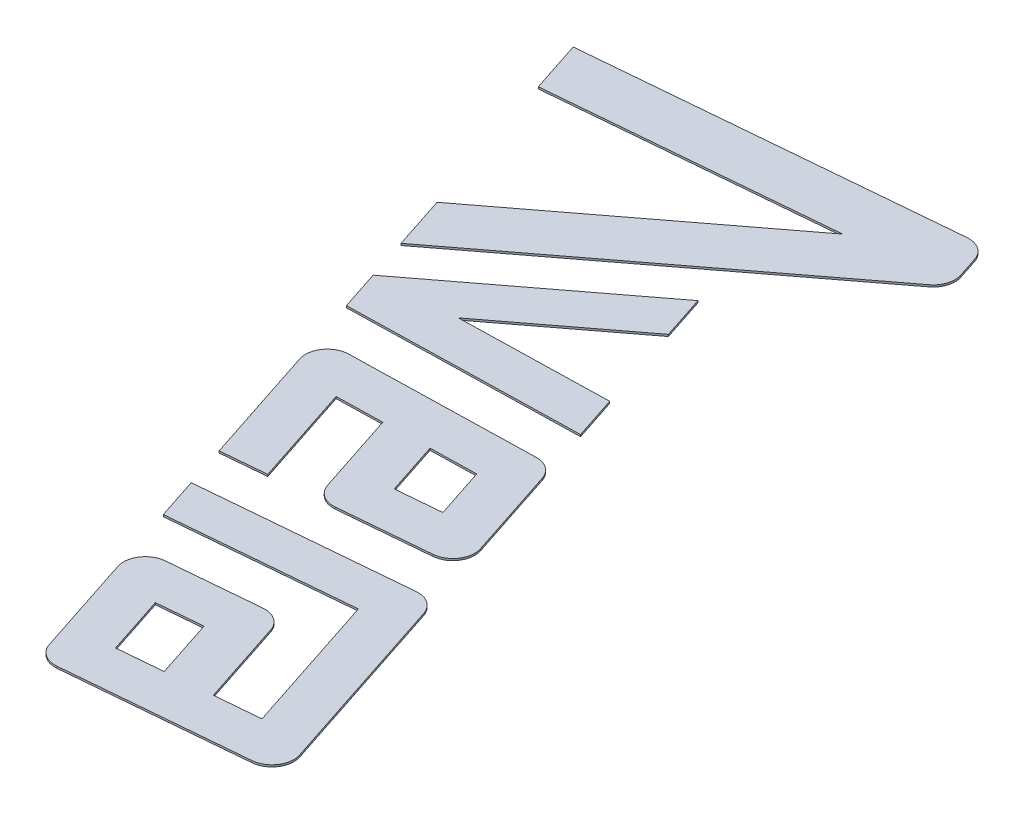
SolidWorks part; units mm, degrees
ref_plane "Front Plane" through (0, 0, 0) normal (0, 0, 1) x (1, 0, 0)
ref_plane "Top Plane" through (0, 0, 0) normal (0, 1, 0) x (1, 0, 0)
ref_plane "Right Plane" through (0, 0, 0) normal (1, 0, 0) x (0, 0, -1)
sketch "Sketch1" plane through (0, 0, 0) normal (0, 1, 0) x (1, 0, 0)
  line L0 (6.2636, 13.3847) -> (6.9802, 11.1991) construction
  line L2 (6.9802, 11.1991) -> (16.6844, 18.5822)
  line L4 (6.9802, 11.1991) -> (7.6656, 9.1086)
  line L5 (19.6969, 9.3941) -> (20.4135, 7.2086) construction
  line L6 (7.6656, 9.1086) -> (19.6969, 9.3941)
  line L10 (7.6656, 9.1086) -> (8.3822, 6.9231) construction
  line L11 (19.5596, 7.1883) -> (9.93, 6.9598)
  line L15 (19.6969, 9.3941) -> (18.9484, 11.677)
  line L20 (11.1641, 11.4923) -> (18.9484, 11.677)
  line L21 (11.1641, 11.4923) -> (17.4428, 16.2692)
  line L26 (11.5324, 4.6972) -> (13.2849, -0.6478)
  line L27 (17.4428, 16.2692) -> (16.6844, 18.5822)
  line L32 (13.0803, 4.7339) -> (11.5324, 4.6972)
  line L39 (5.3404, 16.2005) -> (2.7423, 24.1247) construction
  line L45 (17.2762, 2.0125) -> (16.3584, 4.8117)
  line L46 (13.2849, -0.6478) -> (10.9324, -0.855)
  line L56 (13.0821, -7.4116) -> (20.1616, -6.7881) construction
  line L58 (6.2636, 13.3847) -> (5.3404, 16.2005)
  line L59 (17.4595, 25.4208) -> (5.3404, 16.2005)
  line L60 (13.0821, -7.4116) -> (15.5745, -15.0134) construction
  line L61 (15.5745, -15.0134) -> (27.3591, -13.9756) construction
  line L62 (20.4135, 7.2086) -> (8.3822, 6.9231) construction
  line L64 (20.4135, 7.2086) -> (22.717, 0.1828) construction
  line L65 (8.8645, 5.4519) -> (10.9324, -0.855)
  line L66 (18.7602, 4.8687) -> (16.3584, 4.8117)
  line L68 (20.6796, 6.3969) -> (22.2656, 1.5595)
  line L69 (14.2003, 3.9425) -> (15.3531, 0.4267)
  line L71 (18.7602, 4.8687) -> (19.6287, 2.2197)
  line L72 (19.6287, 2.2197) -> (17.2762, 2.0125)
  line L73 (21.2738, 0.0557) -> (16.5467, -0.3606)
  line L74 (22.717, 0.1828) -> (10.9324, -0.855) construction
  line L75 (18.7602, 4.8687) -> (8.4367, 4.6237) construction
  line L76 (11.6489, -3.0405) -> (12.3655, -5.2261)
  line L77 (19.6287, 2.2197) -> (10.7306, 1.4361) construction
  line L78 (10.9324, -0.855) -> (11.6489, -3.0405) construction
  line L79 (11.6489, -3.0405) -> (22.5243, -2.0828)
  line L80 (12.3655, -5.2261) -> (21.7976, -4.3954)
  line L81 (23.718, -2.8701) -> (26.9077, -12.5989)
  line L82 (21.7976, -4.3954) -> (24.2708, -11.9387)
  line L83 (12.3655, -5.2261) -> (13.0821, -7.4116) construction
  line L84 (20.446, -7.6555) -> (21.9183, -12.1459)
  line L85 (14.5253, -7.2845) -> (19.2524, -6.8682)
  line L86 (13.5335, -8.7884) -> (15.2901, -14.1461)
  line L87 (16.4837, -14.9334) -> (25.9159, -14.1027)
  line L88 (21.2481, -2.7193) -> (25.1736, -14.6922) construction
  line L89 (17.1912, -12.5622) -> (19.5438, -12.355)
  line L90 (23.4336, -2.0027) -> (27.3591, -13.9756) construction
  line L91 (15.3727, -12.7223) -> (27.1574, -11.6845) construction
  line L92 (16.1704, -9.4485) -> (17.1912, -12.5622)
  line L93 (16.1704, -9.4485) -> (18.5229, -9.2414)
  line L95 (16.1704, -9.4485) -> (17.76, -14.2969) construction
  line L96 (18.5449, -9.2394) -> (19.7327, -12.8624) construction
  line L97 (21.9183, -12.1459) -> (24.2708, -11.9387)
  line L98 (1.8466, 26.8566) -> (2.7423, 24.1247)
  line L99 (16.1704, -9.4485) -> (18.5449, -9.2394) construction
  line L100 (18.5229, -9.2414) -> (19.5438, -12.355)
  line L101 (20.1616, -6.7881) -> (21.9183, -12.1459) construction
  line L102 (14.2003, 3.9425) -> (13.9342, 4.7542)
  line L103 (13.0803, 4.7339) -> (13.9342, 4.7542)
  line L105 (17.4595, 25.4208) -> (2.7423, 24.1247)
  line L106 (22.4342, 26.6593) -> (22.0779, 27.746)
  line L107 (22.0377, 25.3858) -> (6.2636, 13.3847)
  line L109 (20.8842, 28.5333) -> (1.8466, 26.8566)
  arc A0 (14.5253, -7.2845) -> (13.5335, -8.7884) centre (14.6262, -8.4301) ccw
  arc A1 (16.4837, -14.9334) -> (15.2901, -14.1461) centre (16.3829, -13.7878) cw
  arc A2 (22.0377, 25.3858) -> (22.4342, 26.6593) centre (21.3414, 26.301) ccw
  arc A3 (22.0779, 27.746) -> (20.8842, 28.5333) centre (20.9851, 27.3877) ccw
  arc A5 (9.93, 6.9598) -> (8.8645, 5.4519) centre (9.9573, 5.8101) ccw
  arc A6 (19.5596, 7.1883) -> (20.6796, 6.3969) centre (19.5868, 6.0387) cw
  arc A7 (25.9159, -14.1027) -> (26.9077, -12.5989) centre (25.815, -12.9572) ccw
  arc A8 (23.718, -2.8701) -> (22.5243, -2.0828) centre (22.6252, -3.2284) ccw
  arc A9 (16.5467, -0.3606) -> (15.3531, 0.4267) centre (16.4458, 0.785) cw
  arc A10 (21.2738, 0.0557) -> (22.2656, 1.5595) centre (21.1729, 1.2013) ccw
  arc A11 (19.2524, -6.8682) -> (20.446, -7.6555) centre (19.3533, -8.0138) cw
  dimension "D1" = 1.15
  dimension "D2" = 1.15
extrude "Boss-Extrude1" add sketch "Sketch1" along normal blind 0.1
